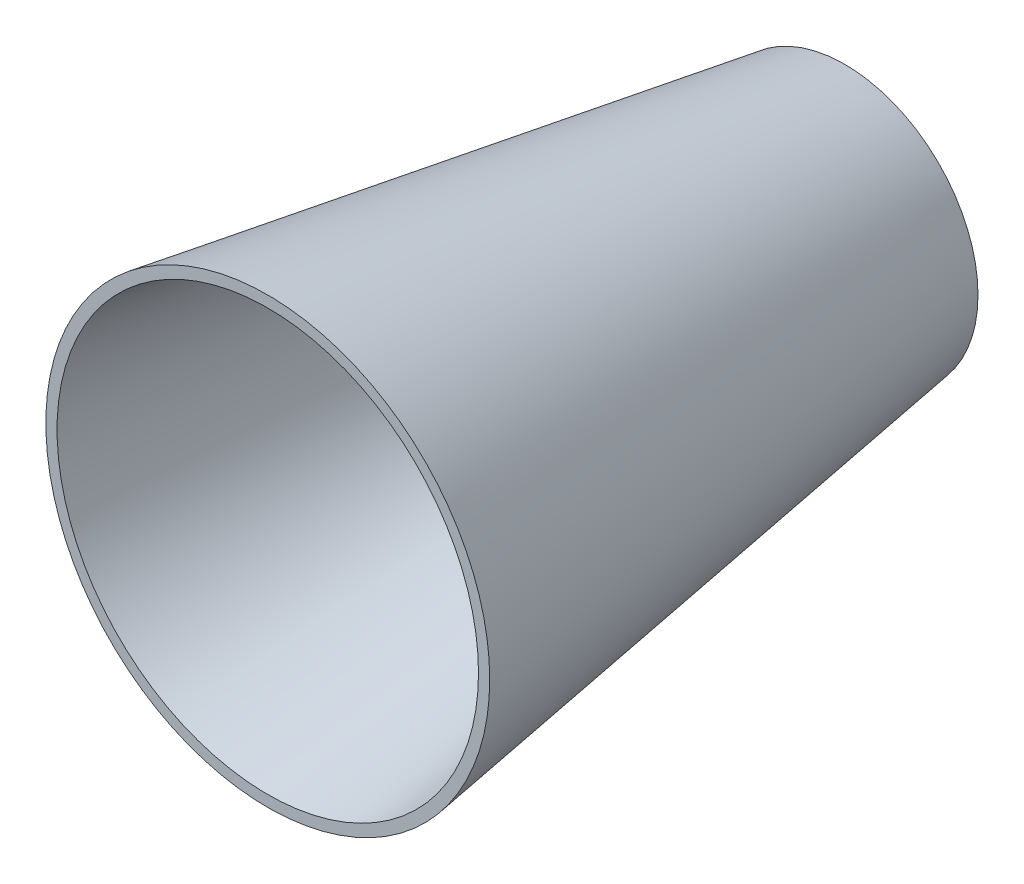
SolidWorks part; units mm, degrees
ref_plane "Plan de face" through (0, 0, 0) normal (0, 0, 1) x (1, 0, 0)
ref_plane "Plan de dessus" through (0, 0, 0) normal (0, 1, 0) x (1, 0, 0)
ref_plane "Plan de droite" through (0, 0, 0) normal (1, 0, 0) x (0, 0, -1)
sketch "Esquisse1" plane through (0, 0, 0) normal (0, 0, 1) x (1, 0, 0)
  circle A0 centre (0, 0) radius 30
  dimension "D1" = 60
ref_plane "Plan1" through (0, 0, 130) normal (0, 0, 1) x (1, 0, 0)
sketch "Esquisse2" plane through (0, 0, 130) normal (0, 0, 1) x (1, 0, 0)
  circle A0 centre (0, 0) radius 50
  dimension "D1" = 100
loft "Lissage1" add profiles "Esquisse1", "Esquisse2"
shell "Coque1" thickness 2.5
